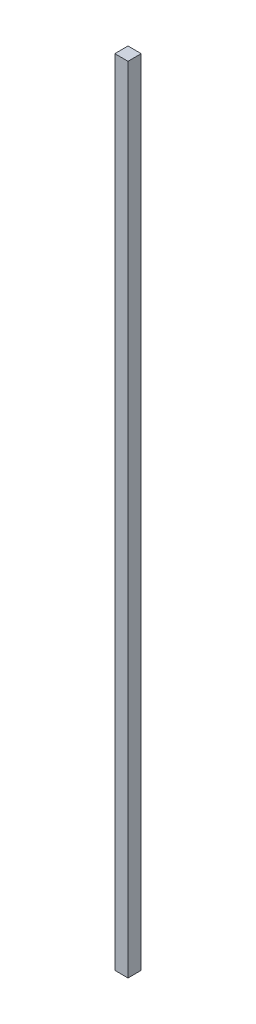
SolidWorks part; units mm, degrees
ref_plane "Front Plane" through (0, 0, 0) normal (0, 0, 1) x (1, 0, 0)
ref_plane "Top Plane" through (0, 0, 0) normal (0, 1, 0) x (1, 0, 0)
ref_plane "Right Plane" through (0, 0, 0) normal (1, 0, 0) x (0, 0, -1)
sketch "Sketch1" plane through (0, 0, 0) normal (0, 1, 0) x (1, 0, 0)
  line L1 (0, 0) -> (25.4, 0)
  line L2 (0, 0) -> (0, -25.4)
  line L3 (0, -25.4) -> (25.4, -25.4)
  line L4 (25.4, 0) -> (25.4, -25.4)
  dimension "D1" = 25.4
  dimension "D2" = 25.4
extrude "Boss-Extrude1" add sketch "Sketch1" along normal blind 1524 contours L1 L4 L3 L2
